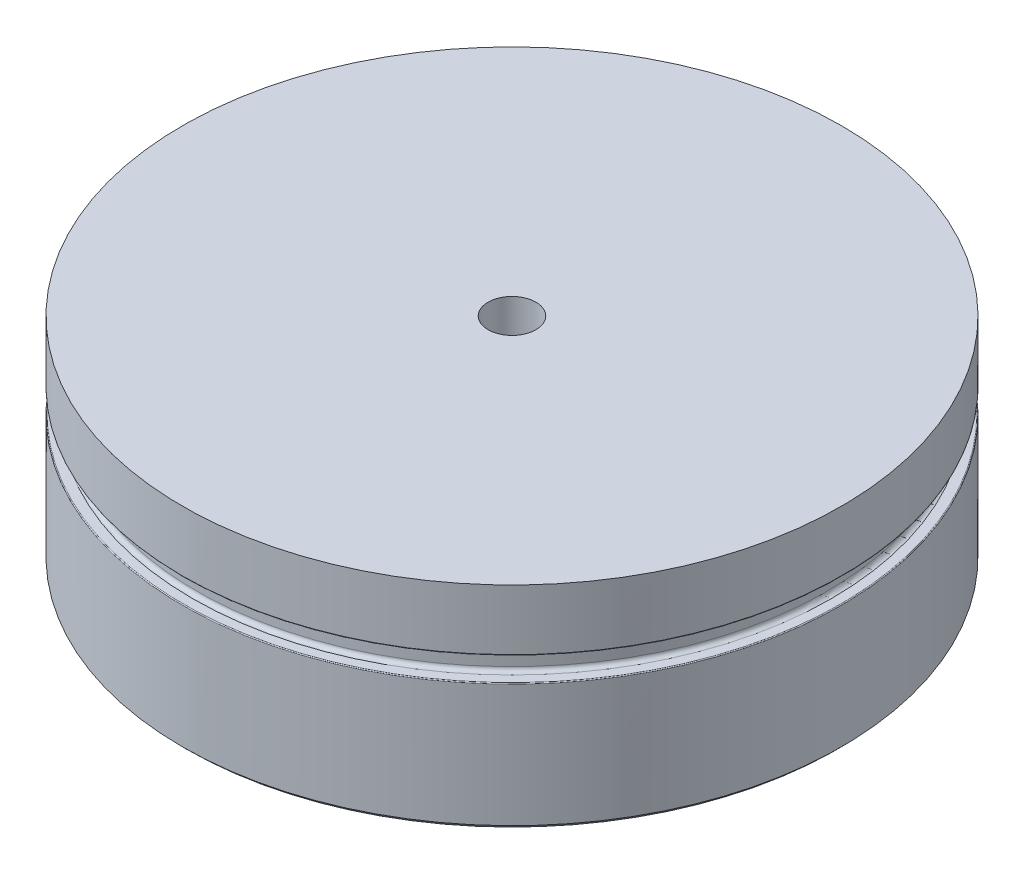
SolidWorks part; units mm, degrees
ref_plane "Front Plane" through (0, 0, 0) normal (0, 0, 1) x (1, 0, 0)
ref_plane "Top Plane" through (0, 0, 0) normal (0, 1, 0) x (1, 0, 0)
ref_plane "Right Plane" through (0, 0, 0) normal (1, 0, 0) x (0, 0, -1)
sketch "Sketch1" plane through (0, 0, 0) normal (0, 0, 1) x (1, 0, 0)
  line L0 (0, 0) -> (0, 32183.2735) construction
  line L1 (0, 0) -> (0, 63.5)
  line L2 (0, 63.5) -> (-98.3869, 63.5)
  line L3 (-98.3869, 63.5) -> (-98.3869, 45.2374)
  line L4 (-98.3869, 45.2374) -> (-94.107, 45.2374)
  line L5 (-94.107, 45.2374) -> (-94.107, 38.1)
  line L6 (-94.107, 38.1) -> (-98.3869, 38.1)
  line L7 (-98.3869, 38.1) -> (-98.3869, 6.5512)
  line L9 (-98.3869, 6.5512) -> (-98.3869, 0)
  line L10 (-98.3869, 0) -> (0, 0)
  point P5 (0, 0)
  dimension "D3" = 188.214
  dimension "D4" = 196.7738
  dimension "D5" = 7.1374
  dimension "D6" = 63.5
  dimension "D7" = 38.1
revolve "Revolve1" add sketch "Sketch1" angle 360 about L0
fillet "Fillet1" radius 1.27 2 edges at (0, 45.2374, -94.107) (0, 38.1, -94.107)
fillet "Fillet2" radius 0.254 2 edges at (0, 38.1, -98.3869) (0, 45.2374, -98.3869)
chamfer "Chamfer1" distance 1.27 angle 45 1 edges at (0, 0, -98.3869)
hole_wizard "3/8 NPT Tapped Hole3" positions "Sketch6" profile "Sketch7" size "3/8" standard "ANSI Inch" end condition through all
sketch "Sketch6" plane through (0, 0, 0) normal (0, -1, 0) x (1, 0, 0)
  point P0 (0, 0)
sketch "Sketch7" plane through (0, 0, 0) normal (1, 0, 0) x (0, 0, -1)
  line L0 (0, 0) -> (0, 63.5)
  line L1 (0, 63.5) -> (7.1374, 63.5)
  line L2 (-8.25, 10.3378) -> (-8.5727, 0) construction
  line L3 (7.1374, 63.5) -> (7.1374, 10.3378)
  line L4 (7.1374, 10.3378) -> (8.25, 10.3378)
  line L5 (8.25, 10.3378) -> (8.5727, 0)
  line L7 (8.5727, 0) -> (0, 0)
  line L8 (0, -6.35) -> (0, 107.95) construction
  line L11 (-7.1374, 10.3378) -> (-8.25, 10.3378) construction
  dimension "Thru Tap Drill Dia." = 14.2748
  dimension "Thru Tap Drill Depth" = 63.5
  dimension "Thread Dia." = 17.1455
  dimension "Thread Angle" = 3.576
  dimension "Thread Depth" = 10.3378
